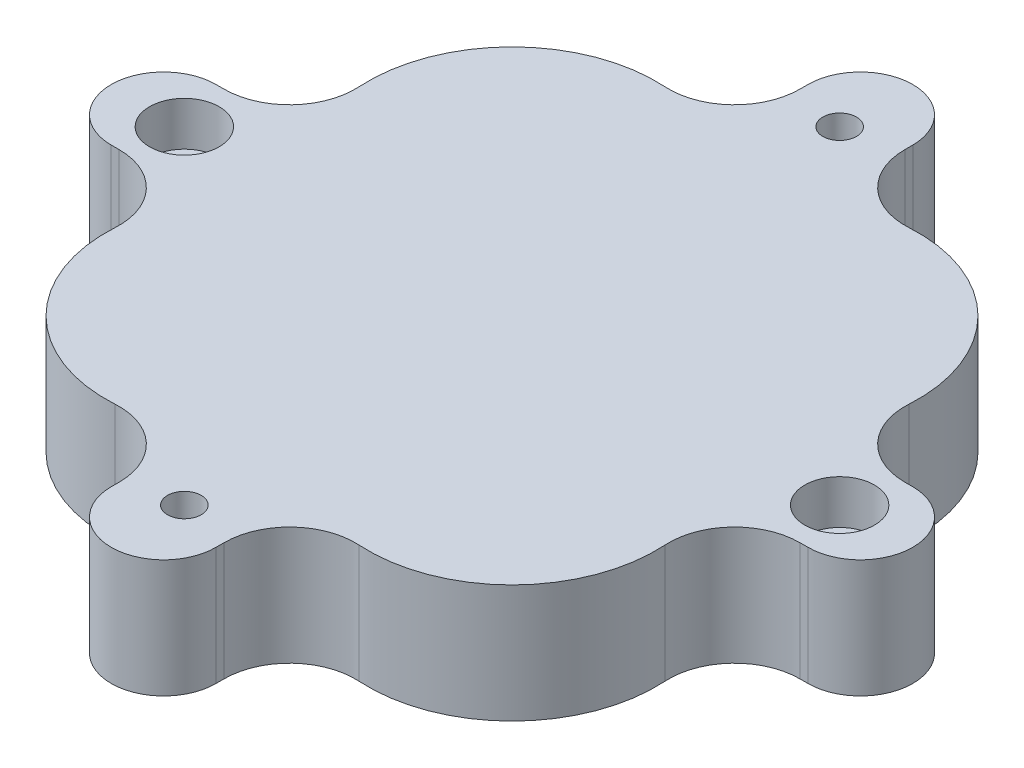
SolidWorks part; units mm, degrees
ref_plane "Front Plane" through (0, 0, 0) normal (0, 0, 1) x (1, 0, 0)
ref_plane "Top Plane" through (0, 0, 0) normal (0, 1, 0) x (1, 0, 0)
ref_plane "Right Plane" through (0, 0, 0) normal (1, 0, 0) x (0, 0, -1)
sketch "Sketch5" plane through (0, 0, 0) normal (0, -1, 0) x (-1, 0, 0)
  line L0 (33.7599, -5.08) -> (32.9803, -5.08)
  line L1 (33.7599, 5.08) -> (32.9803, 5.08)
  line L2 (5.08, -33.7599) -> (5.08, -32.9803)
  line L3 (-5.08, -33.7599) -> (-5.08, -32.9803)
  line L4 (-33.7599, -5.08) -> (-32.9803, -5.08)
  line L5 (-33.7599, 5.08) -> (-32.9803, 5.08)
  line L6 (-5.08, 33.7599) -> (-5.08, 32.9803)
  line L7 (5.08, 33.7599) -> (5.08, 32.9803)
  arc A0 (-26.6427, -11.8269) -> (-11.8269, -26.6427) centre (-12.7, -12.7) ccw
  arc A2 (26.6427, 11.8269) -> (11.8269, 26.6427) centre (12.7, 12.7) ccw
  arc A3 (11.8269, -26.6427) -> (26.6427, -11.8269) centre (12.7, -12.7) ccw
  arc A4 (-11.8269, 26.6427) -> (-26.6427, 11.8269) centre (-12.7, 12.7) ccw
  arc A5 (33.7599, 5.08) -> (33.7599, -5.08) centre (33.7599, 0) cw
  arc A6 (33.7599, -5.08) -> (38.8399, 0) centre (33.7599, 0) ccw construction
  arc A7 (32.9803, 5.08) -> (26.6427, 11.8269) centre (32.9803, 11.43) cw
  arc A8 (26.6427, -11.8269) -> (32.9803, -5.08) centre (32.9803, -11.43) cw
  arc A9 (5.08, -32.9803) -> (11.8269, -26.6427) centre (11.43, -32.9803) cw
  arc A10 (5.08, -33.7599) -> (-5.08, -33.7599) centre (0, -33.7599) cw
  arc A11 (-11.8269, -26.6427) -> (-5.08, -32.9803) centre (-11.43, -32.9803) cw
  arc A12 (-32.9803, -5.08) -> (-26.6427, -11.8269) centre (-32.9803, -11.43) cw
  arc A13 (-33.7599, -5.08) -> (-33.7599, 5.08) centre (-33.7599, 0) cw
  arc A14 (-26.6427, 11.8269) -> (-32.9803, 5.08) centre (-32.9803, 11.43) cw
  arc A15 (-5.08, 32.9803) -> (-11.8269, 26.6427) centre (-11.43, 32.9803) cw
  arc A16 (-5.08, 33.7599) -> (5.08, 33.7599) centre (0, 33.7599) cw
  arc A17 (11.8269, 26.6427) -> (5.08, 32.9803) centre (11.43, 32.9803) cw
  point P55 (0, 0)
  dimension "D1" = 6.35
  dimension "D2" = 4
extrude "Boss-Extrude4" add sketch "Sketch5" along normal blind 3.81 and the other way blind 7.62
sketch "Sketch21" plane through (0, -3.81, 0) normal (0, -1, 0) x (1, 0, 0)
  line L8 (12.0253, 23.4739) -> (-12.0253, 23.4739)
  line L9 (-23.4739, 12.0253) -> (-23.4739, -12.0253)
  line L10 (-12.0253, -23.4739) -> (12.0253, -23.4739)
  line L11 (23.4739, -12.0253) -> (23.4739, 12.0253)
  line L16 (-33.7599, -1.905) -> (-32.9803, -1.905)
  line L17 (-1.905, -32.9803) -> (-1.905, -33.7599)
  line L18 (1.905, -33.7599) -> (1.905, -32.9803)
  line L19 (32.9803, -1.905) -> (33.7599, -1.905)
  line L20 (33.7599, 1.905) -> (32.9803, 1.905)
  line L21 (1.905, 32.9803) -> (1.905, 33.7599)
  line L22 (-1.905, 33.7599) -> (-1.905, 32.9803)
  line L23 (-32.9803, 1.905) -> (-33.7599, 1.905)
  line L24 (-33.7599, -1.905) -> (-32.9803, -1.905)
  line L25 (-1.905, -32.9803) -> (-1.905, -33.7599)
  line L26 (1.905, -33.7599) -> (1.905, -32.9803)
  line L27 (32.9803, -1.905) -> (33.7599, -1.905)
  line L28 (33.7599, 1.905) -> (32.9803, 1.905)
  line L29 (1.905, 32.9803) -> (1.905, 33.7599)
  line L30 (-1.905, 33.7599) -> (-1.905, 32.9803)
  line L31 (-32.9803, 1.905) -> (-33.7599, 1.905)
  arc A32 (-33.7599, 1.905) -> (-33.7599, -1.905) centre (-33.7599, 0) ccw
  arc A33 (-23.4739, -12.0253) -> (-32.9803, -1.905) centre (-32.9803, -11.43) ccw
  arc A34 (-23.4739, -12.0253) -> (-12.0253, -23.4739) centre (-12.7, -12.7) ccw
  arc A35 (-1.905, -32.9803) -> (-12.0253, -23.4739) centre (-11.43, -32.9803) ccw
  arc A36 (-1.905, -33.7599) -> (1.905, -33.7599) centre (0, -33.7599) ccw
  arc A37 (12.0253, -23.4739) -> (1.905, -32.9803) centre (11.43, -32.9803) ccw
  arc A38 (12.0253, -23.4739) -> (23.4739, -12.0253) centre (12.7, -12.7) ccw
  arc A39 (32.9803, -1.905) -> (23.4739, -12.0253) centre (32.9803, -11.43) ccw
  arc A40 (33.7599, -1.905) -> (33.7599, 1.905) centre (33.7599, 0) ccw
  arc A41 (23.4739, 12.0253) -> (32.9803, 1.905) centre (32.9803, 11.43) ccw
  arc A42 (23.4739, 12.0253) -> (12.0253, 23.4739) centre (12.7, 12.7) ccw
  arc A43 (1.905, 32.9803) -> (12.0253, 23.4739) centre (11.43, 32.9803) ccw
  arc A44 (1.905, 33.7599) -> (-1.905, 33.7599) centre (0, 33.7599) ccw
  arc A45 (-12.0253, 23.4739) -> (-1.905, 32.9803) centre (-11.43, 32.9803) ccw
  arc A46 (-12.0253, 23.4739) -> (-23.4739, 12.0253) centre (-12.7, 12.7) ccw
  arc A47 (-32.9803, 1.905) -> (-23.4739, 12.0253) centre (-32.9803, 11.43) ccw
  arc A48 (-33.7599, 1.905) -> (-33.7599, -1.905) centre (-33.7599, 0) ccw
  arc A49 (-23.4739, -12.0253) -> (-32.9803, -1.905) centre (-32.9803, -11.43) ccw
  arc A50 (-23.4739, -12.0253) -> (-12.0253, -23.4739) centre (-12.7, -12.7) ccw
  arc A51 (-1.905, -32.9803) -> (-12.0253, -23.4739) centre (-11.43, -32.9803) ccw
  arc A52 (-1.905, -33.7599) -> (1.905, -33.7599) centre (0, -33.7599) ccw
  arc A53 (12.0253, -23.4739) -> (1.905, -32.9803) centre (11.43, -32.9803) ccw
  arc A54 (12.0253, -23.4739) -> (23.4739, -12.0253) centre (12.7, -12.7) ccw
  arc A55 (32.9803, -1.905) -> (23.4739, -12.0253) centre (32.9803, -11.43) ccw
  arc A56 (33.7599, -1.905) -> (33.7599, 1.905) centre (33.7599, 0) ccw
  arc A57 (23.4739, 12.0253) -> (32.9803, 1.905) centre (32.9803, 11.43) ccw
  arc A58 (23.4739, 12.0253) -> (12.0253, 23.4739) centre (12.7, 12.7) ccw
  arc A59 (1.905, 32.9803) -> (12.0253, 23.4739) centre (11.43, 32.9803) ccw
  arc A60 (1.905, 33.7599) -> (-1.905, 33.7599) centre (0, 33.7599) ccw
  arc A61 (-12.0253, 23.4739) -> (-1.905, 32.9803) centre (-11.43, 32.9803) ccw
  arc A62 (-12.0253, 23.4739) -> (-23.4739, 12.0253) centre (-12.7, 12.7) ccw
  arc A63 (-32.9803, 1.905) -> (-23.4739, 12.0253) centre (-32.9803, 11.43) ccw
  dimension "D1" = 3.175
extrude "Cut-Extrude1" cut sketch "Sketch21" against normal blind 4.445 contours A63 L9 A49 A50 A51 L10 A53 A54 A55 L11 A57 A58 A59 L8 A61 A62
hole_wizard "CBORE for #4 Binding Head Machine Screw3" positions "Sketch32" profile "Sketch33" counterbore size "#4" standard "ANSI Inch" end condition through all
sketch "Sketch32" plane through (0, -3.81, 0) normal (0, -1, 0) x (-1, 0, 0)
  point P0 (0, 31.75)
  point P2 (0, -31.75)
  dimension "D1" = 31.75
  dimension "D2" = 31.75
sketch "Sketch33" plane through (0, -3.81, -31.75) normal (1, 0, 0) x (0, 0, -1)
  line L0 (0, 0) -> (0, 11.43)
  line L1 (0, 11.43) -> (1.6319, 11.43)
  line L3 (1.6319, 11.43) -> (1.632, 4.2672)
  line L4 (1.632, 4.2672) -> (3.3731, 4.2672)
  line L5 (3.3731, 4.2672) -> (3.3731, 0)
  line L7 (3.3731, 0) -> (0, 0)
  line L11 (0, -6.35) -> (0, 107.95) construction
  dimension "Thru Hole Dia." = 3.2639
  dimension "Thru Hole Depth" = 11.43
  dimension "C'Bore Dia." = 6.7462
  dimension "C'Bore Depth" = 4.2672
hole_wizard "CBORE for #4 Binding Head Machine Screw4" positions "Sketch34" profile "Sketch35" counterbore size "#4" standard "ANSI Inch" end condition through all
sketch "Sketch34" plane through (0, 7.62, 0) normal (0, 1, 0) x (1, 0, 0)
  point P0 (31.75, 0)
  point P2 (-31.75, 0)
  dimension "D1" = 31.75
  dimension "D2" = 31.75
sketch "Sketch35" plane through (31.75, 7.62, 0) normal (1, 0, 0) x (0, 0, 1)
  line L0 (0, 0) -> (0, 11.43)
  line L1 (0, 11.43) -> (1.6319, 11.43)
  line L3 (1.6319, 11.43) -> (1.632, 4.2672)
  line L4 (1.632, 4.2672) -> (3.3731, 4.2672)
  line L5 (3.3731, 4.2672) -> (3.3731, 0)
  line L7 (3.3731, 0) -> (0, 0)
  line L11 (0, -6.35) -> (0, 107.95) construction
  dimension "Thru Hole Dia." = 3.2639
  dimension "Thru Hole Depth" = 11.43
  dimension "C'Bore Dia." = 6.7462
  dimension "C'Bore Depth" = 4.2672
